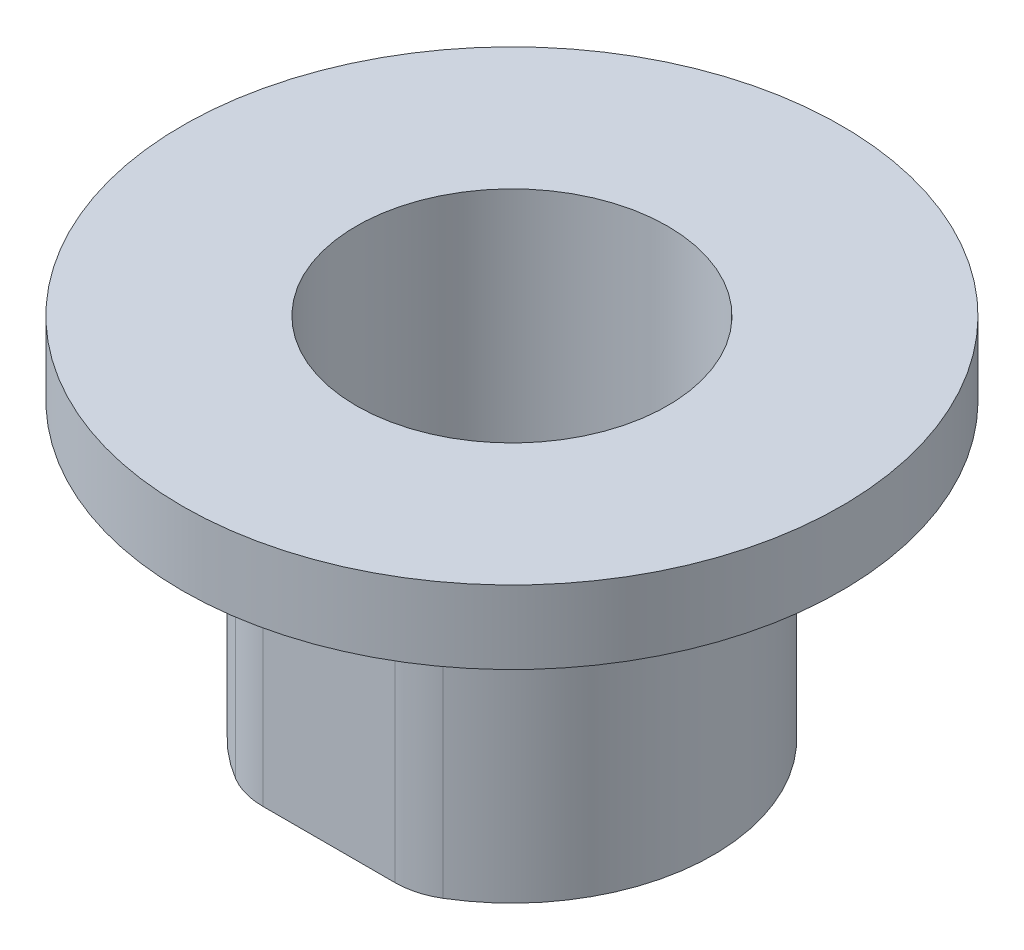
SolidWorks part; units mm, degrees
material "CA"
ref_plane "Front Plane" through (0, 0, 0) normal (0, 0, 1) x (1, 0, 0)
ref_plane "Top Plane" through (0, 0, 0) normal (0, 1, 0) x (1, 0, 0)
ref_plane "Right Plane" through (0, 0, 0) normal (1, 0, 0) x (0, 0, -1)
sketch "Sketch1" plane through (0, 0, 0) normal (0, 1, 0) x (1, 0, 0)
  line L0 (1.8028, -5) -> (-1.8028, -5)
  circle A0 centre (0, 0) radius 5.5 construction
  arc A1 (-2.8329, -4.7143) -> (2.8329, -4.7143) centre (0, 0) cw
  arc A2 (-1.8028, -5) -> (-2.8329, -4.7143) centre (-1.8028, -3) cw
  arc A3 (2.8329, -4.7143) -> (1.8028, -5) centre (1.8028, -3) cw
  point P5 (0, -5.5)
  point P7 (0, 0)
  point P9 (-2.2913, -5)
  point P12 (2.2913, -5)
  dimension "D1" = 11
  dimension "D3" = 2
  dimension "D2" = 0.5
extrude "Boss-Extrude1" add sketch "Sketch1" along normal blind 10 contours L0 A2 A1 A3
sketch "Sketch2" plane through (0, 10, 0) normal (0, 1, 0) x (1, 0, 0)
  circle A0 centre (0, 0) radius 4.25
  dimension "D1" = 8.5
extrude "Cut-Extrude1" cut sketch "Sketch2" against normal blind 9
sketch "Sketch3" plane through (0, 10, 0) normal (0, 1, 0) x (1, 0, 0)
  line L0 (1.8028, -5) -> (-1.8028, -5) construction
  line L1 (1.8028, -5) -> (-1.8028, -5)
  circle A0 centre (0, 0) radius 9
  arc A1 (1.8028, -5) -> (2.8329, -4.7143) centre (1.8028, -3) ccw construction
  arc A2 (-2.8329, -4.7143) -> (-1.8028, -5) centre (-1.8028, -3) ccw construction
  arc A3 (2.8329, -4.7143) -> (-2.8329, -4.7143) centre (0, 0) ccw construction
  arc A4 (1.8028, -5) -> (2.8329, -4.7143) centre (1.8028, -3) ccw
  arc A5 (-2.8329, -4.7143) -> (-1.8028, -5) centre (-1.8028, -3) ccw
  arc A6 (2.8329, -4.7143) -> (-2.8329, -4.7143) centre (0, 0) ccw
  dimension "D1" = 18
extrude "Boss-Extrude2" add sketch "Sketch3" against normal blind 2
